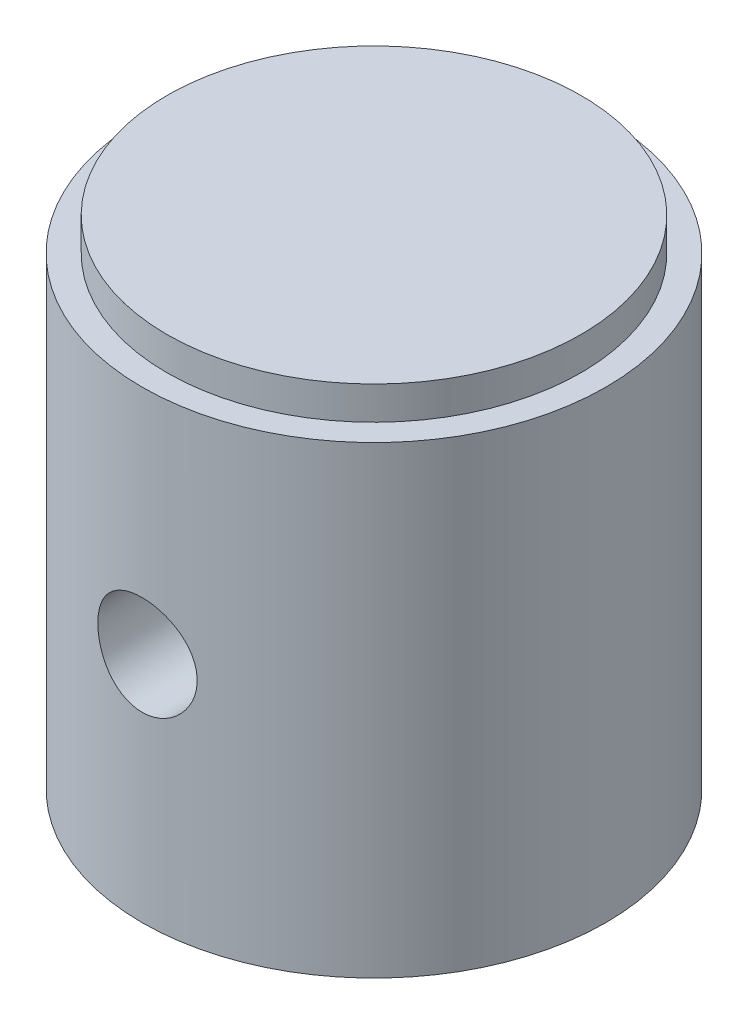
SolidWorks part; units mm, degrees
ref_plane "Front Plane" through (0, 0, 0) normal (0, 0, 1) x (1, 0, 0)
ref_plane "Top Plane" through (0, 0, 0) normal (0, 1, 0) x (1, 0, 0)
ref_plane "Right Plane" through (0, 0, 0) normal (1, 0, 0) x (0, 0, -1)
sketch "Sketch1" plane through (0, 0, 0) normal (0, 0, 1) x (1, 0, 0)
  line L0 (0, 0) -> (0, 1.1459) construction
  line L1 (0, 0) -> (0, -5.6536) construction
  line L2 (0, 1.1459) -> (-6.25, 1.1459)
  line L3 (-6.25, 1.1459) -> (-6.25, 0.1459)
  line L4 (-6.25, 0.1459) -> (-7, 0.1459)
  line L5 (-7, 0.1459) -> (-7, -13.8541)
  line L6 (-7, -13.8541) -> (-6.25, -13.8541)
  line L7 (-6.25, -13.8541) -> (-4.75, -9.7329)
  line L8 (-4.75, -9.7329) -> (-4.75, -2.8541)
  line L9 (-4.75, -2.8541) -> (0, 0)
  line L10 (0, 0) -> (0, 1.1459)
  dimension "D1" = 7
  dimension "D2" = 6.25
  dimension "D3" = 1
  dimension "D4" = 15
  dimension "D5" = 6.25
  dimension "D6" = 4.75
  dimension "D7" = 20
  dimension "D8" = 59
  dimension "D9" = 11
revolve "Revolve1" add sketch "Sketch1" angle 360 about L1
sketch "Sketch2" plane through (0, 0, 0) normal (0, 0, 1) x (1, 0, 0)
  line L0 (-7, -13.8541) -> (7, -13.8541) construction
  circle A0 centre (0, -6.8541) radius 1.5
  dimension "D1" = 3
  dimension "D2" = 7
extrude "Cut-Extrude1" cut sketch "Sketch2" against normal through all and the other way through all
